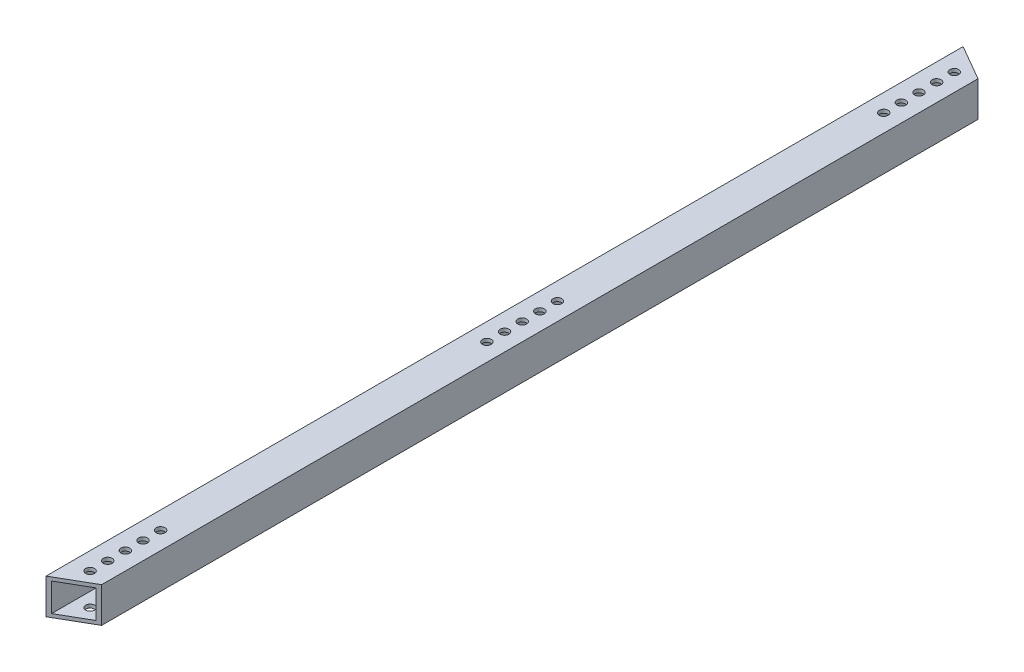
SolidWorks part; units mm, degrees
ref_plane "Front Plane" through (0, 0, 0) normal (0, 0, 1) x (1, 0, 0)
ref_plane "Top Plane" through (0, 0, 0) normal (0, 1, 0) x (1, 0, 0)
ref_plane "Right Plane" through (0, 0, 0) normal (1, 0, 0) x (0, 0, -1)
sketch "Sketch1" plane through (0, 0, 0) normal (0, 0, 1) x (1, 0, 0)
  line L0 (-10.16, 10.16) -> (10.16, 10.16)
  line L1 (-12.7, -12.7) -> (12.7, -12.7)
  line L2 (-12.7, -12.7) -> (-12.7, 12.7)
  line L3 (-12.7, 12.7) -> (12.7, 12.7)
  line L4 (12.7, -12.7) -> (12.7, 12.7)
  line L5 (-12.7, -12.7) -> (12.7, 12.7) construction
  line L6 (-12.7, 12.7) -> (12.7, -12.7) construction
  line L7 (10.16, -10.16) -> (10.16, 10.16)
  line L8 (-10.16, -10.16) -> (10.16, -10.16)
  line L9 (-10.16, -10.16) -> (-10.16, 10.16)
  point P0 (0, 0)
  dimension "D1" = 25.4
  dimension "D2" = 25.4
  dimension "D3" = 2.54
extrude "Boss-Extrude2" add sketch "Sketch1" along normal blind 660.4
sketch "Sketch2" plane through (0, 12.7, 0) normal (0, 1, 0) x (1, 0, 0)
  line L0 (-12.7, -660.4) -> (12.7, -645.7353)
  line L1 (12.7, -660.4) -> (12.7, 0) construction
  line L2 (12.7, -645.7353) -> (12.7, -660.4)
  line L3 (12.7, -660.4) -> (-12.7, -660.4)
  line L4 (-12.7, -330.2) -> (12.7, -330.2) construction
  line L5 (-12.7, -660.4) -> (-12.7, 0) construction
  line L6 (12.7, 0) -> (-12.7, 0)
  line L7 (12.7, -14.6647) -> (12.7, 0)
  line L8 (-12.7, 0) -> (12.7, -14.6647)
  dimension "D1" = 30
extrude "Cut-Extrude1" cut sketch "Sketch2" against normal through all
sketch "Sketch3" plane through (0, 12.7, 0) normal (0, 1, 0) x (1, 0, 0)
  line L0 (0, -7.3323) -> (0, -653.0677) construction
  line L1 (-12.7, 0) -> (12.7, -14.6647) construction
  line L2 (12.7, -645.7353) -> (-12.7, -660.4) construction
  line L3 (12.7, -330.2) -> (-12.7, -330.2) construction
  line L4 (12.7, -645.7353) -> (12.7, -14.6647) construction
  line L5 (-12.7, -660.4) -> (-12.7, 0) construction
  circle A0 centre (0, -330.2) radius 3.175
  circle A1 centre (0, -317.5) radius 3.175
  circle A2 centre (0, -304.8) radius 3.175
  circle A3 centre (0, -355.6) radius 3.175
  circle A4 centre (0, -342.9) radius 3.175
  circle A5 centre (0, -641.35) radius 3.175
  circle A6 centre (0, -628.65) radius 3.175
  circle A7 centre (0, -615.95) radius 3.175
  circle A8 centre (0, -603.25) radius 3.175
  circle A9 centre (0, -590.55) radius 3.175
  circle A10 centre (0, -69.85) radius 3.175
  circle A11 centre (0, -57.15) radius 3.175
  circle A12 centre (0, -44.45) radius 3.175
  circle A13 centre (0, -31.75) radius 3.175
  circle A14 centre (0, -19.05) radius 3.175
  dimension "D1" = 6.35
  dimension "D3" = 6.35
  dimension "D4" = 311.15
  dimension "D2" = 3
  dimension "D5" = 5
extrude "Cut-Extrude2" cut sketch "Sketch3" against normal through all
